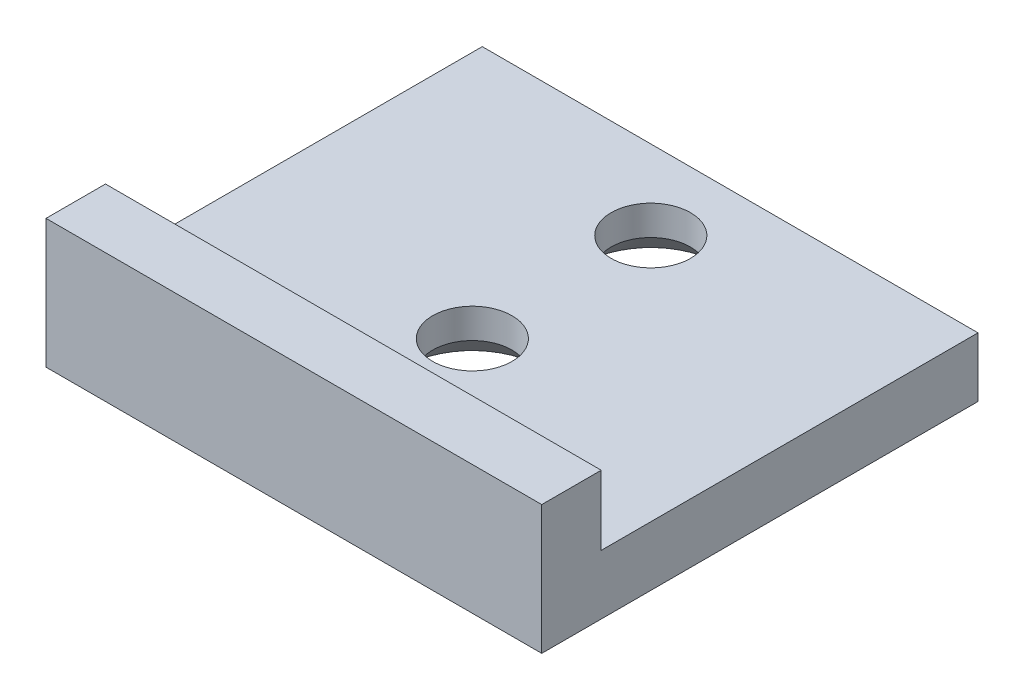
SolidWorks part; units mm, degrees
ref_plane "Front Plane" through (0, 0, 0) normal (0, 0, 1) x (1, 0, 0)
ref_plane "Top Plane" through (0, 0, 0) normal (0, 1, 0) x (1, 0, 0)
ref_plane "Right Plane" through (0, 0, 0) normal (1, 0, 0) x (0, 0, -1)
sketch "Sketch1" plane through (0, 0, 0) normal (0, 1, 0) x (1, 0, 0)
  line L1 (-25, -22) -> (25, -22)
  line L2 (-25, -22) -> (-25, 22)
  line L3 (-25, 22) -> (25, 22)
  line L4 (25, -22) -> (25, 22)
  line L5 (-25, -22) -> (25, 22) construction
  line L6 (-25, 22) -> (25, -22) construction
  point P0 (0, 0)
  dimension "D1" = 50
  dimension "D2" = 44
extrude "Boss-Extrude1" add sketch "Sketch1" along normal mid plane 13
sketch "Sketch2" plane through (25, 0, 0) normal (1, 0, 0) x (0, 0, -1)
  line L0 (-16, 6.5) -> (-16, -0.5)
  line L1 (-22, 6.5) -> (22, 6.5) construction
  line L2 (-16, -0.5) -> (22, -0.5)
  line L3 (22, 6.5) -> (22, -6.5) construction
  line L4 (22, -0.5) -> (22, 6.5)
  line L5 (22, 6.5) -> (-16, 6.5)
  line L6 (-22, 6.5) -> (-22, -6.5) construction
  line L7 (-22, -6.5) -> (22, -6.5) construction
  dimension "D1" = 6
  dimension "D2" = 6
extrude "Cut-Extrude1" cut sketch "Sketch2" against normal through all
hole_wizard "Ø8.0mm Dowel Hole1" positions "Sketch3" profile "Sketch4" hole size "Ø8.0" standard "ISO" end condition up to next
sketch "Sketch3" plane through (0, -6.5, 0) normal (0, -1, 0) x (-1, 0, 0)
  line L0 (-25, 22) -> (25, 22) construction
  point P0 (0, 14)
  point P2 (0, -4)
  point P6 (0, 0)
  dimension "D1" = 8
  dimension "D2" = 18
sketch "Sketch4" plane through (0, -6.5, -14) normal (1, 0, 0) x (0, 0, -1)
  line L0 (0, 0) -> (0, 6)
  line L1 (0, 6) -> (4, 6)
  line L2 (4, 6) -> (4, 0)
  line L5 (4, 0) -> (0, 0)
  line L11 (0, -6.35) -> (0, 107.95) construction
  dimension "Thru Hole Dia." = 8
  dimension "Thru Hole Depth" = 6
chamfer "Chamfer1" distance 3 angle 45 2 edges at (0, -6.5, 0) (0, -6.5, -18)
